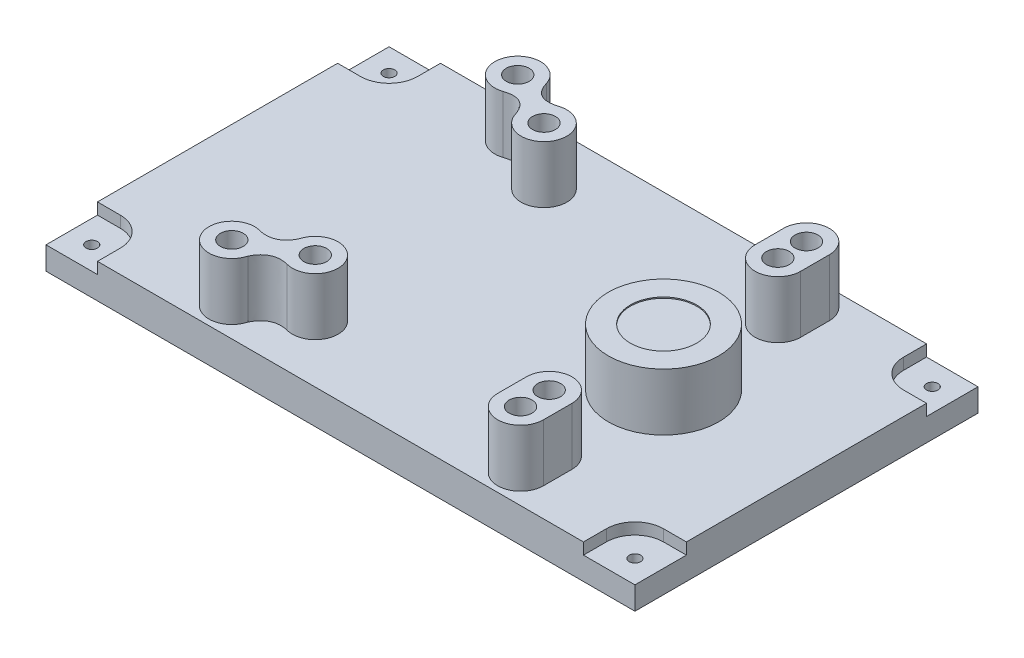
SolidWorks part; units mm, degrees
ref_plane "Front Plane" through (0, 0, 0) normal (0, 0, 1) x (1, 0, 0)
ref_plane "Top Plane" through (0, 0, 0) normal (0, 1, 0) x (1, 0, 0)
ref_plane "Right Plane" through (0, 0, 0) normal (1, 0, 0) x (0, 0, -1)
sketch "Sketch2" plane through (0, 0, 0) normal (0, 1, 0) x (1, 0, 0)
  line L0 (-511.4332, 138.9503) -> (-511.4332, 702.2836) construction
  line L1 (0, 0) -> (103, 0)
  line L2 (0, 0) -> (0, 60)
  line L3 (0, 60) -> (103, 60)
  line L4 (103, 0) -> (103, 60)
  dimension "D1" = 60
  dimension "D2" = 103
extrude "Boss-Extrude1" add sketch "Sketch2" along normal blind 6
sketch "Sketch3" plane through (0, 6, 0) normal (0, 1, 0) x (1, 0, 0)
  line L0 (0, 30) -> (103, 30) construction
  line L1 (0, 60) -> (0, 0) construction
  line L2 (103, 0) -> (103, 60) construction
  line L3 (78, 68.8667) -> (78, -10.4705) construction
  line L4 (78, 55) -> (78, 50) construction
  line L5 (82, 55) -> (82, 50)
  line L6 (74, 55) -> (74, 50)
  line L7 (27.5, 55) -> (37.0901, 50) construction
  line L8 (27.5, 5) -> (37.0901, 10) construction
  line L9 (78, 10) -> (78, 5) construction
  line L10 (82, 10) -> (82, 5)
  line L11 (74, 10) -> (74, 5)
  circle A0 centre (78, 55) radius 2
  circle A1 centre (78, 50) radius 2
  circle A2 centre (78, 30) radius 9.65
  circle A3 centre (78, 10) radius 2
  circle A4 centre (78, 5) radius 2
  arc A5 (82, 55) -> (74, 55) centre (78, 55) ccw
  arc A6 (74, 50) -> (82, 50) centre (78, 50) ccw
  circle A7 centre (37.0901, 50) radius 2
  circle A8 centre (37.0901, 10) radius 2
  circle A9 centre (27.5, 5) radius 2
  circle A10 centre (27.5, 55) radius 2
  arc A11 (36.0176, 6.1465) -> (33.3166, 11.3269) centre (37.0901, 10) ccw
  arc A12 (28.8476, 8.7662) -> (31.3593, 3.9486) centre (27.5, 5) ccw
  arc A13 (31.3558, 56.0644) -> (28.8349, 51.2293) centre (27.5, 55) ccw
  arc A14 (33.2763, 48.7937) -> (35.8956, 53.8175) centre (37.0901, 50) ccw
  circle A15 centre (27.5, 5) radius 4 construction
  circle A16 centre (37.0901, 10) radius 4 construction
  circle A17 centre (27.5, 55) radius 4 construction
  circle A18 centre (37.0901, 50) radius 4 construction
  arc A19 (82, 10) -> (74, 10) centre (78, 10) ccw
  arc A20 (74, 5) -> (82, 5) centre (78, 5) ccw
  spline S0 degree 2 poles (28.8476, 8.7662) (32.1223, 8.2795) (33.3166, 11.3269) knots 0 0 0 1 1 1
  spline S1 degree 2 poles (31.3593, 3.9486) (32.8352, 6.912) (36.0176, 6.1465) knots 0 0 0 1 1 1
  spline S2 degree 2 poles (31.3199, 56.1867) (32.2975, 52.7326) (35.8956, 53.8175) knots 0 0 0 1 1 1
  spline S3 degree 2 poles (28.7141, 51.1887) (32.1058, 52.3648) (33.2763, 48.7937) knots 0 0 0 1 1 1
  point P16 (78, 52.5)
  point P55 (78, 7.5)
  dimension "D1" = 19.3
  dimension "D4" = 4
  dimension "D5" = 40
  dimension "D10" = 4
  dimension "D11" = 4
  dimension "D2" = 8
  dimension "D3" = 25
  dimension "D6" = 20
  dimension "D7" = 20
  dimension "D8" = 5
  dimension "D9" = 5
  dimension "D12" = 27.5
  dimension "D13" = 2
extrude "Boss-Extrude2" add sketch "Sketch3" along normal blind 10 contours A2 | L6 A6 L5 A5 A0 A1 | L11 A20 L10 A19 A3 A4 | A12 S1 A11 S0 A8 A9 | A13 S3 A14 S2 A7 A10
sketch "Sketch5" plane through (0, 6, 0) normal (0, 1, 0) x (1, 0, 0)
  line L0 (0, 0) -> (103, 0) construction
  line L1 (9, 0) -> (0, 0)
  line L2 (9, 0) -> (9, 4)
  line L3 (4, 9) -> (0, 9)
  line L4 (0, 0) -> (0, 9)
  line L5 (0, 60) -> (0, 0) construction
  line L7 (0, 30) -> (122.4782, 30) construction
  line L8 (51.5, 0) -> (51.5, 60) construction
  line L9 (103, 60) -> (0, 60) construction
  line L10 (0, 60) -> (0, 51)
  line L11 (4, 51) -> (0, 51)
  line L12 (9, 60) -> (9, 56)
  line L13 (9, 60) -> (0, 60)
  line L14 (94, 60) -> (103, 60)
  line L15 (94, 60) -> (94, 56)
  line L16 (99, 51) -> (103, 51)
  line L17 (103, 60) -> (103, 51)
  line L18 (103, 0) -> (103, 9)
  line L19 (99, 9) -> (103, 9)
  line L20 (94, 0) -> (94, 4)
  line L21 (94, 0) -> (103, 0)
  arc A0 (4, 9) -> (9, 4) centre (4, 4) cw
  arc A1 (4, 51) -> (9, 56) centre (4, 56) ccw
  arc A2 (99, 51) -> (94, 56) centre (99, 56) cw
  arc A3 (99, 9) -> (94, 4) centre (99, 4) ccw
  dimension "D3" = 5
  dimension "D1" = 9
  dimension "D2" = 9
extrude "Cut-Extrude1" cut sketch "Sketch5" against normal blind 2
sketch "Sketch6" plane through (0, 4, 0) normal (0, 1, 0) x (1, 0, 0)
  circle A0 centre (4, 4) radius 1
  circle A1 centre (4, 56) radius 1
  circle A2 centre (99, 56) radius 1
  circle A3 centre (99, 4) radius 1
  dimension "D1" = 2
extrude "Cut-Extrude2" cut sketch "Sketch6" against normal through all
sketch "Sketch7" plane through (0, 16, 0) normal (0, 1, 0) x (1, 0, 0)
  circle A1 centre (78, 30) radius 5.8
extrude "Cut-Extrude3" cut sketch "Sketch7" against normal blind 0.2
